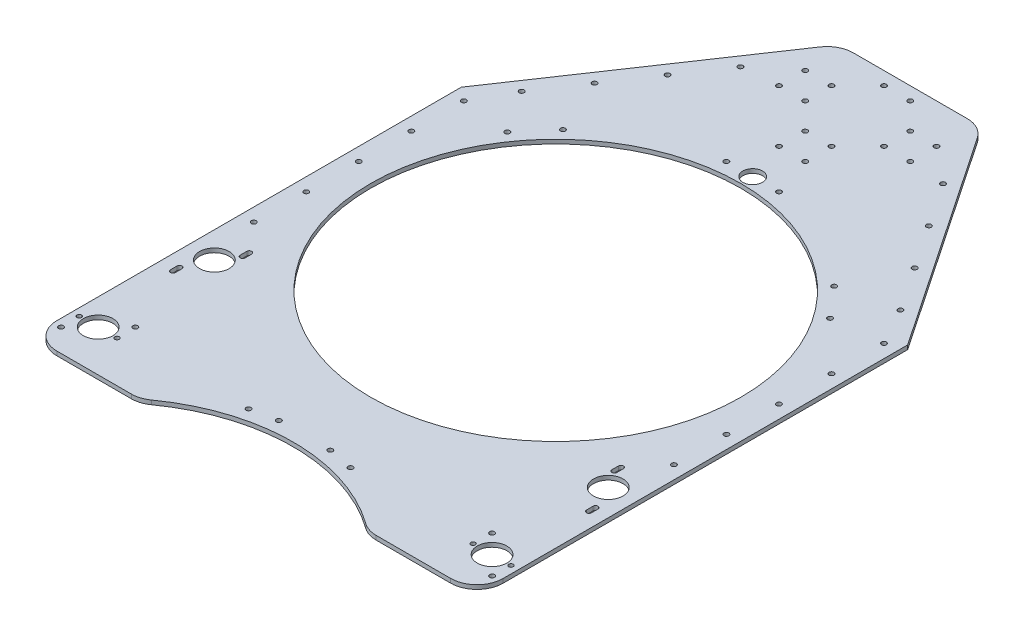
SolidWorks part; units mm, degrees
other "Markup1"
sketch "Sketch21" plane through (215.9, 4, 342.9) normal (0.1673, 0.7898, 0.5901) x (0.9857, -0.1221, -0.116)
material "Thornel Mat VMA"
ref_plane "Front Plane" through (0, 0, 0) normal (0, 0, 1) x (1, 0, 0)
ref_plane "Top Plane" through (0, 0, 0) normal (0, 1, 0) x (1, 0, 0)
ref_plane "Right Plane" through (0, 0, 0) normal (1, 0, 0) x (0, 0, -1)
sketch "Sketch1" plane through (0, 0, 0) normal (0, 1, 0) x (1, 0, 0)
  line L1 (-215.9, 342.9) -> (215.9, 342.9)
  line L2 (-215.9, 342.9) -> (-215.9, -342.9)
  line L3 (-215.9, -342.9) -> (215.9, -342.9)
  line L4 (215.9, 342.9) -> (215.9, -342.9)
  line L5 (-215.9, 342.9) -> (215.9, -342.9) construction
  line L6 (-215.9, -342.9) -> (215.9, 342.9) construction
  point P0 (0, 0)
  dimension "D1" = 431.8
  dimension "D2" = 685.8
extrude "Boss-Extrude1" add sketch "Sketch1" along normal blind 4
sketch "Sketch2" plane through (0, 4, 0) normal (0, 1, 0) x (1, 0, 0)
  line L0 (0, -342.9) -> (0, 342.9) construction
  line L1 (-215.9, -342.9) -> (215.9, -342.9) construction
  line L2 (215.9, 342.9) -> (-215.9, 342.9) construction
  line L3 (-215.9, 342.9) -> (-215.9, -342.9) construction
  line L4 (-208.4605, -320.8555) -> (-190.5, -302.895) construction
  line L5 (-193.1461, -302.895) -> (-215.9, -302.895) construction
  line L6 (190.5, -215.9) -> (190.5, -165.1) construction
  line L7 (190.5, -190.5) -> (201.2345, -213.5202) construction
  line L8 (201.2345, -213.5202) -> (179.7655, -167.4798) construction
  line L9 (-208.4605, -320.8555) -> (-172.5395, -284.9345) construction
  line L10 (203.6158, -219.8702) -> (203.6158, -213.5202)
  line L11 (198.8533, -219.8702) -> (198.8533, -213.5202)
  line L12 (182.1467, -173.8298) -> (182.1467, -167.4798)
  line L13 (177.3842, -173.8298) -> (177.3842, -167.4798)
  line L14 (-198.8533, -219.8702) -> (-198.8533, -213.5202)
  line L15 (-203.6158, -219.8702) -> (-203.6158, -213.5202)
  line L16 (-177.3842, -173.8298) -> (-177.3842, -167.4798)
  line L17 (-182.1467, -173.8298) -> (-182.1467, -167.4798)
  circle A0 centre (-190.5, -302.895) radius 14.3129
  circle A1 centre (-190.5, -190.5) radius 14.3129
  circle A3 centre (190.5, -190.5) radius 14.3129
  circle A4 centre (190.5, -190.5) radius 25.4 construction
  circle A5 centre (-190.5, -190.5) radius 25.4 construction
  circle A6 centre (201.2345, -213.5202) radius 2.3812
  circle A7 centre (179.7655, -167.4798) radius 2.3813
  circle A10 centre (-190.5, -302.895) radius 25.4 construction
  circle A11 centre (-208.4605, -320.8555) radius 2.3813
  circle A15 centre (-172.5395, -284.9345) radius 2.3813
  circle A16 centre (172.5395, -284.9345) radius 2.3813
  circle A17 centre (208.4605, -320.8555) radius 2.3813
  circle A18 centre (190.5, -302.895) radius 14.3129
  circle A19 centre (-179.7655, -167.4798) radius 2.3813
  circle A20 centre (-201.2345, -213.5202) radius 2.3813
  circle A21 centre (208.788, -302.895) radius 2.159
  circle A22 centre (172.212, -302.895) radius 2.159
  circle A23 centre (-172.212, -302.895) radius 2.159
  circle A24 centre (-208.788, -302.895) radius 2.159
  circle A25 centre (179.7655, -173.8298) radius 2.3813
  circle A26 centre (201.2345, -219.8702) radius 2.3813
  circle A27 centre (-201.2345, -219.8702) radius 2.3813
  circle A28 centre (-179.7655, -173.8298) radius 2.3813
  point P33 (-190.5, -304.8)
  point P34 (-189.5475, -303.8475)
  point P48 (190.5, -302.895)
  dimension "D1" = 28.6258
  dimension "D2" = 28.6258
  dimension "D6" = 50.8
  dimension "D7" = 50.8
  dimension "D8" = 4.7625
  dimension "D9" = 4.7625
  dimension "D10" = 18.288
  dimension "D11" = 4.318
  dimension "D12" = 50.8
  dimension "D13" = 4.7625
  dimension "D18" = 4.7625
  dimension "D20" = 4.7625
  dimension "D3" = 40.005
  dimension "D4" = 112.395
  dimension "D5" = 25.4
  dimension "D15" = 45
  dimension "D16" = 25
  dimension "D19" = 6.35
  dimension "D21" = 6.35
  dimension "D14" = 2
  dimension "D17" = 2
extrude "Cut-Extrude1" cut sketch "Sketch2" against normal through all contours A18 | A17 | A21 | A22 | A16 | A26 | A26 L10 A6 L11 | A6 | A3 | A25 | A25 L12 A7 L13 | A7 | A19 | A28 | L17 A28 L16 A19 | A1 | A20 | A27 | A0 | A11 | A24 | A23 | A15 | L15 A27 L14 A20
sketch "Sketch3" plane through (0, 0, 0) normal (0, -1, 0) x (-1, 0, 0)
  line L1 (29.8706, 270.2084) -> (-24.7394, 270.2084)
  line L2 (29.8706, 270.2084) -> (29.8706, 216.2334)
  line L3 (29.8706, 216.2334) -> (-24.7394, 216.2334)
  line L4 (-24.7394, 270.2084) -> (-24.7394, 216.2334)
  line L5 (29.8706, 270.2084) -> (-24.7394, 216.2334) construction
  line L6 (29.8706, 216.2334) -> (-24.7394, 270.2084) construction
  point P0 (2.5656, 243.2209)
  dimension "D1" = 53.975
  dimension "D2" = 54.61
extrude "Boss-Extrude2" [suppressed] add sketch "Sketch3" along normal blind 203.2
fillet "Fillet1" [suppressed] radius 20.32
sketch "Sketch4" [suppressed] plane through (0, -203.2, 0) normal (0, -1, 0) x (-1, 0, 0)
  line L0 (-24.7394, 216.2334) -> (29.8706, 216.2334) construction
  line L1 (26.6956, 267.0334) -> (-21.5644, 267.0334)
  line L2 (26.6956, 267.0334) -> (26.6956, 219.4084)
  line L3 (26.6956, 219.4084) -> (-21.5644, 219.4084)
  line L4 (-21.5644, 267.0334) -> (-21.5644, 219.4084)
  line L5 (26.6956, 267.0334) -> (-21.5644, 219.4084) construction
  line L6 (26.6956, 219.4084) -> (-21.5644, 267.0334) construction
  line L7 (29.8706, 270.2084) -> (-24.7394, 270.2084) construction
  line L8 (29.8706, 216.2334) -> (29.8706, 270.2084) construction
  line L9 (-24.7394, 270.2084) -> (-24.7394, 216.2334) construction
  point P0 (2.5656, 243.2209)
  dimension "D1" = 3.175
  dimension "D2" = 3.175
  dimension "D3" = 3.175
  dimension "D4" = 3.175
extrude "Cut-Extrude2" [suppressed] cut sketch "Sketch4" against normal blind 203.2
sketch "Sketch5" [suppressed] plane through (-29.8706, 0, 0) normal (-1, 0, 0) x (0, 0, 1)
  line L0 (-216.2334, -203.2) -> (-216.2334, 0) construction
  line L1 (-216.2334, -203.2) -> (-270.2084, -203.2) construction
  circle A0 centre (-243.2209, -184.15) radius 14.2875
  dimension "D1" = 28.575
  dimension "D2" = 26.9875
  dimension "D3" = 19.05
extrude "Cut-Extrude3" [suppressed] cut sketch "Sketch5" against normal blind 203.2
sketch "Sketch6" plane through (0, 4, 0) normal (0, 1, 0) x (1, 0, 0)
  circle A0 centre (0, -50.8) radius 179.07
  dimension "D1" = 358.14
  dimension "D2" = 50.8
extrude "Cut-Extrude4" cut sketch "Sketch6" against normal through all
sketch "Sketch8" plane through (0, 4, 0) normal (0, 1, 0) x (1, 0, 0)
  circle A0 centre (0, 139.7) radius 9.525
  circle A2 centre (0, 139.7) radius 25.4 construction
  circle A3 centre (25.4, 139.7) radius 2.3813
  circle A4 centre (-25.4, 139.7) radius 2.3813
  dimension "D1" = 19.05
  dimension "D3" = 50.8
  dimension "D4" = 4.7625
  dimension "D5" = 4.7625
  dimension "D2" = 139.7
extrude "Cut-Extrude6" cut sketch "Sketch8" against normal through all
fillet "Fillet2" radius 25.4 2 edges at (215.9, 2, 342.9) (-215.9, 2, 342.9)
sketch "Sketch10" plane through (0, 4, 0) normal (0, 1, 0) x (1, 0, 0)
  line L0 (-215.9, 342.9) -> (-215.9, -317.5) construction
  line L1 (215.9, -317.5) -> (215.9, 342.9) construction
  circle A0 centre (-190.5, 215.9) radius 14.3129
  circle A1 centre (190.5, 215.9) radius 14.3129
  circle A2 centre (-190.5, 215.9) radius 25.4 construction
  circle A3 centre (190.5, 215.9) radius 25.4 construction
  circle A4 centre (190.5, 190.5) radius 2.3813
  circle A5 centre (190.5, 241.3) radius 2.3813
  circle A6 centre (-190.5, 190.5) radius 2.3813
  circle A7 centre (-190.5, 241.3) radius 2.3813
  circle A8 centre (190.5, -190.5) radius 14.3129 construction
  circle A9 centre (-190.5, -190.5) radius 14.3129 construction
  dimension "D1" = 28.6258
  dimension "D2" = 50.8
  dimension "D3" = 28.6258
  dimension "D4" = 50.8
  dimension "D5" = 4.7625
  dimension "D6" = 4.7625
  dimension "D7" = 4.7625
  dimension "D8" = 4.7625
  dimension "D9" = 25.4
  dimension "D10" = 25.4
  dimension "D11" = 406.4
  dimension "D12" = 406.4
extrude "Cut-Extrude8" [suppressed] cut sketch "Sketch10" against normal through all
sketch "Sketch11" plane through (0, 4, 0) normal (0, 1, 0) x (1, 0, 0)
  line L0 (0, -50.8) -> (156.0485, 58.4663) construction
  line L6 (0, 0) -> (0, 139.7) construction
  circle A0 centre (0, -50.8) radius 179.07
  circle A1 centre (0, -50.8) radius 179.07 construction
  circle A2 centre (0, -50.8) radius 184.15
  circle A3 centre (0, -50.8) radius 215.9
  circle A4 centre (156.0485, 58.4663) radius 2.3813
  circle A5 centre (131.1838, 87.3342) radius 2.3813
  circle A6 centre (0, -50.8) radius 190.5 construction
  circle A7 centre (-131.1838, 87.3342) radius 2.3813
  circle A8 centre (-156.0485, 58.4663) radius 2.3813
  dimension "D1" = 368.3
  dimension "D6" = 431.8
  dimension "D7" = 381
  dimension "D9" = 4.7625
  dimension "D10" = 4.7625
  dimension "D2" = 55
  dimension "D8" = 38.1
extrude "Cut-Extrude9" cut sketch "Sketch11" against normal through all contours A4 | A5 | A7 | A8
sketch "Sketch13" plane through (0, 4, 0) normal (0, 1, 0) x (1, 0, 0)
  line L0 (-215.9, 342.9) -> (-215.9, -317.5) construction
  line L1 (215.9, 342.9) -> (-215.9, 342.9) construction
  line L2 (0, -342.9) -> (0, 342.9) construction
  line L3 (-190.5, -342.9) -> (190.5, -342.9) construction
  circle A0 centre (-203.2, 317.5) radius 2.3813
  circle A1 centre (-203.2, 266.7) radius 2.3813
  circle A2 centre (-203.2, 215.9) radius 2.3813
  circle A3 centre (-203.2, 165.1) radius 2.3813
  circle A4 centre (-203.2, 114.3) radius 2.3813
  circle A5 centre (-203.2, 63.5) radius 2.3813
  circle A6 centre (-203.2, 12.7) radius 2.3813
  circle A7 centre (-203.2, -38.1) radius 2.3813
  circle A8 centre (-203.2, -88.9) radius 2.3813
  circle A9 centre (-203.2, -139.7) radius 2.3813
  circle A10 centre (203.2, -139.7) radius 2.3813
  circle A11 centre (203.2, 12.7) radius 2.3813
  circle A12 centre (203.2, 63.5) radius 2.3813
  circle A13 centre (203.2, 114.3) radius 2.3813
  circle A14 centre (203.2, 165.1) radius 2.3813
  circle A15 centre (203.2, 266.7) radius 2.3813
  circle A16 centre (203.2, 317.5) radius 2.3813
  circle A17 centre (-25.4, -330.2) radius 2.4664
  circle A20 centre (-50.8, -330.2) radius 2.3078
  circle A21 centre (50.8, -330.2) radius 2.3078
  circle A22 centre (25.4, -330.2) radius 2.4664
  circle A23 centre (203.2, -88.9) radius 2.3813
  circle A24 centre (203.2, -38.1) radius 2.3813
  circle A25 centre (203.2, 215.9) radius 2.3813
  dimension "D1" = 4.7625
  dimension "D2" = 12.7
  dimension "D3" = 25.4
  dimension "D5" = 25.4
  dimension "D6" = 50.8
  dimension "D7" = 12.7
  dimension "D8" = 12.7
  dimension "D4" = 10
extrude "Cut-Extrude10" cut sketch "Sketch13" against normal through all
sketch "Sketch14" plane through (0, 4, 0) normal (0, 1, 0) x (1, 0, 0)
  line L0 (215.9, -317.5) -> (215.9, 342.9) construction
  line L1 (0, -342.9) -> (0, -229.87) construction
  line L2 (-190.5, -342.9) -> (190.5, -342.9) construction
  circle A0 centre (209.55, -245.745) radius 2.3813
  circle A2 centre (0, -50.8) radius 179.07 construction
  circle A3 centre (-209.55, -245.745) radius 2.3813
  circle A4 centre (190.5, -302.895) radius 14.3129 construction
  dimension "D1" = 57.15
  dimension "D3" = 4.7625
  dimension "D2" = 6.35
extrude "Cut-Extrude11" [suppressed] cut sketch "Sketch14" against normal through all
sketch "Sketch16" plane through (0, 4, 0) normal (0, 1, 0) x (1, 0, 0)
  line L0 (215.9, -317.5) -> (215.9, 342.9) construction
  line L1 (-215.9, 342.9) -> (215.9, 342.9)
  line L2 (-215.9, 342.9) -> (-215.9, 292.1)
  line L3 (-215.9, 292.1) -> (215.9, 292.1)
  line L4 (215.9, 342.9) -> (215.9, 292.1)
  dimension "D1" = 50.8
extrude "Cut-Extrude13" cut sketch "Sketch16" against normal through all
sketch "Sketch17" plane through (0, 0, 0) normal (0, -1, 0) x (-1, 0, 0)
  line L0 (0, -482.6) -> (0, 3.1553) construction
  line L1 (0, -482.6) -> (24.8652, -293.7298) construction
  line L2 (0, -482.6) -> (49.305, -298.5911) construction
  circle A0 centre (0, -482.6) radius 177.8
  circle A1 centre (0, -482.6) radius 190.5 construction
  circle A2 centre (24.8652, -293.7298) radius 2.3813
  circle A3 centre (49.305, -298.5911) radius 2.3813
  circle A4 centre (-24.8652, -293.7298) radius 2.3813
  circle A5 centre (-49.305, -298.5911) radius 2.3813
  dimension "D1" = 355.6
  dimension "D3" = 381
  dimension "D6" = 4.7625
  dimension "D7" = 4.7625
  dimension "D2" = 482.6
  dimension "D4" = 7.5
  dimension "D5" = 15
extrude "Cut-Extrude14" cut sketch "Sketch17" against normal through all
fillet "Fillet3" radius 25.4 2 edges at (-109.9852, 2, 342.9) (109.9852, 2, 342.9)
sketch "Sketch18" plane through (0, 4, 0) normal (0, 1, 0) x (1, 0, 0)
  line L0 (-215.9, 292.1) -> (215.9, 292.1) construction
  line L1 (25.4, 215.9) -> (-25.4, 215.9) construction
  line L2 (25.4, 215.9) -> (25.4, 266.7) construction
  line L3 (25.4, 266.7) -> (-25.4, 266.7) construction
  line L4 (-25.4, 215.9) -> (-25.4, 266.7) construction
  line L5 (25.4, 215.9) -> (-25.4, 266.7) construction
  line L6 (25.4, 266.7) -> (-25.4, 215.9) construction
  line L8 (25.4, 215.9) -> (76.2, 215.9) construction
  line L9 (25.4, 215.9) -> (25.4, 266.7) construction
  line L10 (25.4, 266.7) -> (76.2, 266.7) construction
  line L11 (76.2, 215.9) -> (76.2, 266.7) construction
  circle A0 centre (38.1, 228.6) radius 2.3812
  circle A1 centre (63.5, 228.6) radius 2.3813
  circle A2 centre (63.5, 254) radius 2.3813
  circle A3 centre (38.1, 254) radius 2.3813
  circle A4 centre (-12.7, 177.8) radius 2.3813
  circle A5 centre (-12.7, 203.2) radius 2.3813
  circle A6 centre (12.7, 177.8) radius 2.3813
  circle A7 centre (12.7, 203.2) radius 2.3812
  circle A8 centre (-63.5, 254) radius 2.3812
  circle A9 centre (-38.1, 254) radius 2.3813
  circle A10 centre (-63.5, 228.6) radius 2.3813
  circle A11 centre (-38.1, 228.6) radius 2.3813
  circle A12 centre (12.7, 304.8) radius 2.3812
  circle A13 centre (12.7, 279.4) radius 2.3812
  circle A14 centre (-12.7, 304.8) radius 2.3813
  circle A15 centre (-12.7, 279.4) radius 2.3812
  point P0 (0, 241.3)
  point P45 (0, 241.3)
  dimension "D5" = 4.7625
  dimension "D1" = 50.8
  dimension "D2" = 50.8
  dimension "D3" = 50.8
  dimension "D4" = 12.7
  dimension "D6" = 25.4
  dimension "D9" = 50.8
  dimension "D10" = 4
  dimension "D7" = 2
  dimension "D8" = 2
extrude "Cut-Extrude15" cut sketch "Sketch18" against normal through all
chamfer "Chamfer1" distance 147.32 angle 56 1 edges at (215.9, 2, -292.1)
chamfer "Chamfer2" distance 147.32 angle 56 1 edges at (-215.9, 2, -292.1)
fillet "Fillet4" radius 25.4 2 edges at (68.58, 2, -292.1) (-68.58, 2, -292.1)
sketch "Sketch19" plane through (0, 4, 0) normal (0, 1, 0) x (1, 0, 0)
  line L0 (-76.1321, 280.9035) -> (-215.9, 73.6891) construction
  line L1 (-55.0746, 292.1) -> (55.0746, 292.1) construction
  line L2 (0, 292.1) -> (0, -304.8) construction
  circle A0 centre (-97.9769, 225.806) radius 2.3813
  circle A2 centre (-126.3839, 183.6909) radius 2.3813
  circle A3 centre (-154.7909, 141.5758) radius 2.3813
  circle A4 centre (-183.1979, 99.4607) radius 2.3813
  arc A5 (103.6505, -338.1375) -> (-103.6505, -338.1375) centre (0, -482.6) ccw construction
  circle A6 centre (183.1979, 99.4607) radius 2.3813
  circle A7 centre (154.7909, 141.5758) radius 2.3813
  circle A8 centre (126.3839, 183.6909) radius 2.3812
  circle A9 centre (97.9769, 225.806) radius 2.3813
  dimension "D1" = 12.7
  dimension "D2" = 4.7625
  dimension "D3" = 66.294
  dimension "D4" = 4
extrude "Cut-Extrude16" cut sketch "Sketch19" against normal through all
sketch "Sketch20" plane through (0, 4, 0) normal (0, 1, 0) x (1, 0, 0)
  line L5 (251.0039, -358.5351) -> (-248.9961, -358.5351)
  line L6 (251.0039, -358.5351) -> (251.0039, 241.4649)
  line L7 (251.0039, 241.4649) -> (-248.9961, 241.4649)
  line L8 (-248.9961, -358.5351) -> (-248.9961, 241.4649)
  dimension "D1" = 600
  dimension "D2" = 500
